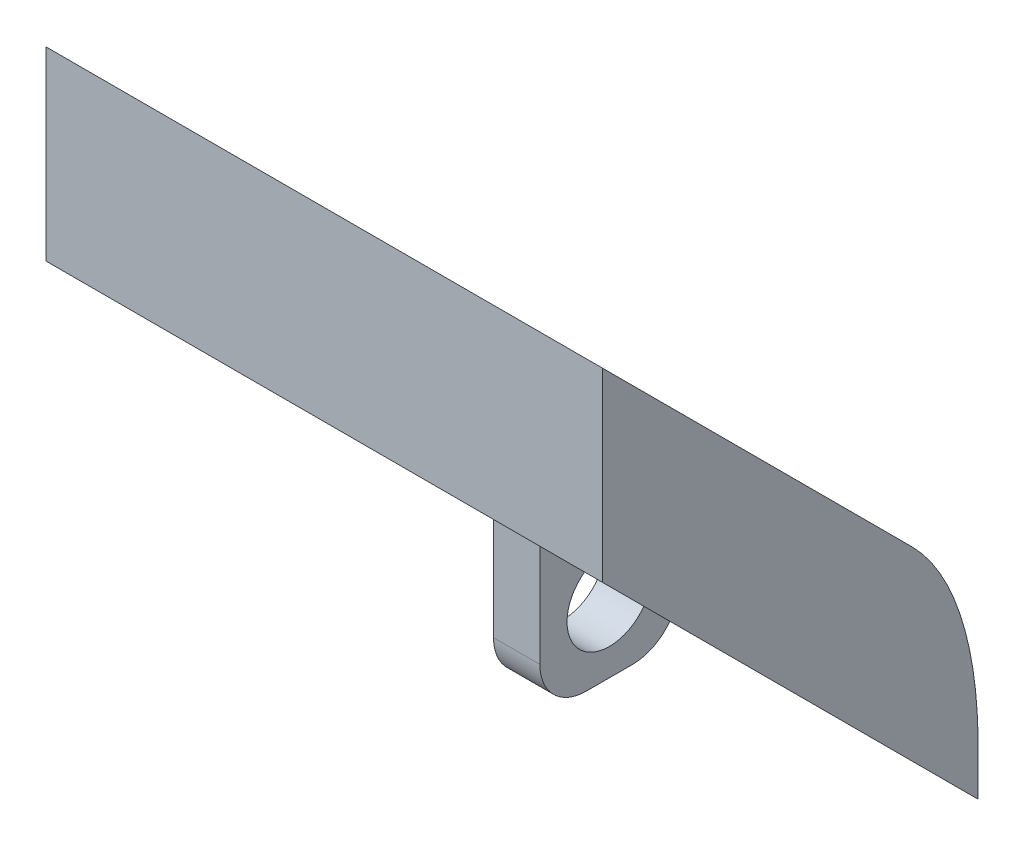
SolidWorks part; units mm, degrees
material "ABS"
ref_plane "Front" through (0, 0, 0) normal (0, 0, 1) x (1, 0, 0)
ref_plane "Top" through (0, 0, 0) normal (0, 1, 0) x (1, 0, 0)
ref_plane "Right" through (0, 0, 0) normal (1, 0, 0) x (0, 0, -1)
sketch "Sketch1" plane through (0, 0, 0) normal (0, 1, 0) x (1, 0, 0)
  line L0 (0, 0) -> (27.1, 83.2)
  line L1 (27.1, 83.2) -> (49.1, 83.2)
  line L2 (49.1, 83.2) -> (76.2, 0)
  line L3 (-50, 0) -> (50, 0) construction
  line L4 (76.2, 0) -> (0, 0)
  dimension "D1" = 76.2
  dimension "D2" = 83.2
  dimension "D3" = 22
extrude "Boss-Extrude1" add sketch "Sketch1" along normal blind 114.3
sketch "Sketch5" plane through (0, 0, 0) normal (0, -1, 0) x (1, 0, 0)
  line L0 (49.1, -83.2) -> (51.38, -76.2)
  line L1 (76.2, 0) -> (49.1, -83.2) construction
  line L2 (51.38, -76.2) -> (24.82, -76.2)
  line L3 (27.1, -83.2) -> (0, 0) construction
  line L4 (24.82, -76.2) -> (27.1, -83.2)
  line L5 (27.1, -83.2) -> (49.1, -83.2)
  dimension "D1" = 7
extrude "Cut-Extrude2" cut sketch "Sketch5" against normal through all
sketch "Sketch2" plane through (0, 0, 0) normal (1, 0, 0) x (0, 0, -1)
  line L0 (0, 114.3) -> (76.2, 38.1)
  line L1 (76.2, 114.3) -> (76.2, 0) construction
  line L2 (76.2, 38.1) -> (76.2, 114.3)
  line L3 (76.2, 114.3) -> (0, 114.3)
  line L4 (0, 88.9) -> (76.2, 12.7)
  line L5 (0, 50) -> (0, -50) construction
  line L7 (76.2, 0) -> (0, 0)
  line L8 (0, 0) -> (0, 88.9)
  line L9 (76.2, 0) -> (76.2, 12.7)
  line L10 (0, 0) -> (76.2, 0) construction
  dimension "D1" = 45
  dimension "D2" = 25.4
extrude "Cut-Extrude1" cut sketch "Sketch2" along normal through all
fillet "Fillet1" radius 45.72 1 edges at (38.1, 38.1, -76.2)
shell "Shell1" thickness 3.175
sketch "Sketch6" plane through (0, 54.9049, -54.9049) normal (0, -0.7071, 0.7071) x (1, 0, 0)
  line L0 (38.1, 13.4869) -> (38.1, -8.0029) construction
  line L1 (34.925, 40.4109) -> (41.275, 40.4109)
  line L2 (34.925, 40.4109) -> (34.925, 13.4869)
  line L3 (34.925, 13.4869) -> (41.275, 13.4869)
  line L4 (41.275, 40.4109) -> (41.275, 13.4869)
  line L5 (53.1339, -8.0029) -> (23.0661, -8.0029) construction
  line L8 (0, 80.8223) -> (76.2, 80.8223) construction
  dimension "D1" = 6.35
  dimension "D2" = 26.924
  dimension "D3" = 40.4114
ref_plane "Plane1" through (38.1, 0, 0) normal (-1, 0, 0) x (0, 0, 1)
sketch "Sketch7" plane through (38.1, 0, 0) normal (-1, 0, 0) x (0, 0, 1)
  line L0 (-35.8492, 73.9607) -> (-35.8492, 23.1607)
  line L1 (-26.3301, 83.4798) -> (-45.3683, 64.4416) construction
  dimension "D1" = 50.8
sweep "Sweep1" add profiles "Sketch6" path "Sketch7"
sketch "Sketch11" plane through (34.925, 0, 0) normal (-1, 0, 0) x (0, 0, 1)
  line L0 (-26.3301, 42.2107) -> (-45.3683, 42.2107)
  line L1 (-26.3301, 83.4798) -> (-26.3301, 32.6798) construction
  line L2 (-45.3683, 64.4416) -> (-45.3683, 13.6416) construction
  line L3 (-45.3683, 42.2107) -> (-45.3683, 13.6416)
  line L4 (-45.3683, 13.6416) -> (-26.3301, 32.6798)
  line L5 (-26.3301, 32.6798) -> (-26.3301, 42.2107)
  line L6 (-35.8492, 73.9607) -> (-35.8492, 42.2107) construction
  line L7 (-26.3301, 83.4798) -> (-45.3683, 64.4416) construction
  line L8 (-26.3301, 32.6798) -> (-45.3683, 13.6416) construction
  dimension "D1" = 31.75
extrude "Cut-Extrude3" cut sketch "Sketch11" against normal up to next
hole_wizard "1/16 (0.457) Dowel Hole1" positions "Sketch14" profile "Sketch13" hole size "1/16" standard "ANSI Inch"
sketch "Sketch14" plane through (34.925, 0, 0) normal (-1, 0, 0) x (0, 0, 1)
  line L0 (-35.8492, 51.7298) -> (-35.8492, 42.2107) construction
  line L1 (-26.3301, 42.2107) -> (-45.3683, 42.2107) construction
  line L3 (-35.8492, 51.7298) -> (-26.3301, 51.7298) construction
  line L4 (-26.3301, 83.4798) -> (-26.3301, 42.2107) construction
  point P0 (-35.8492, 51.7298)
sketch "Sketch13" plane through (34.925, 51.7298, -35.8492) normal (0, 1, 0) x (0, 0, 1)
  line L0 (0, 0) -> (0, 6.35)
  line L1 (0, 6.35) -> (5.8039, 6.35)
  line L2 (5.8039, 6.35) -> (5.8039, 0)
  line L5 (5.8039, 0) -> (0, 0)
  line L11 (0, -6.35) -> (0, 107.95) construction
  dimension "Thru Hole Dia." = 11.6078
  dimension "Thru Hole Depth" = 6.35
fillet "Fillet2" radius 6.35 2 edges at (38.1, 42.2107, -45.3683) (38.1, 42.2107, -26.3301)
